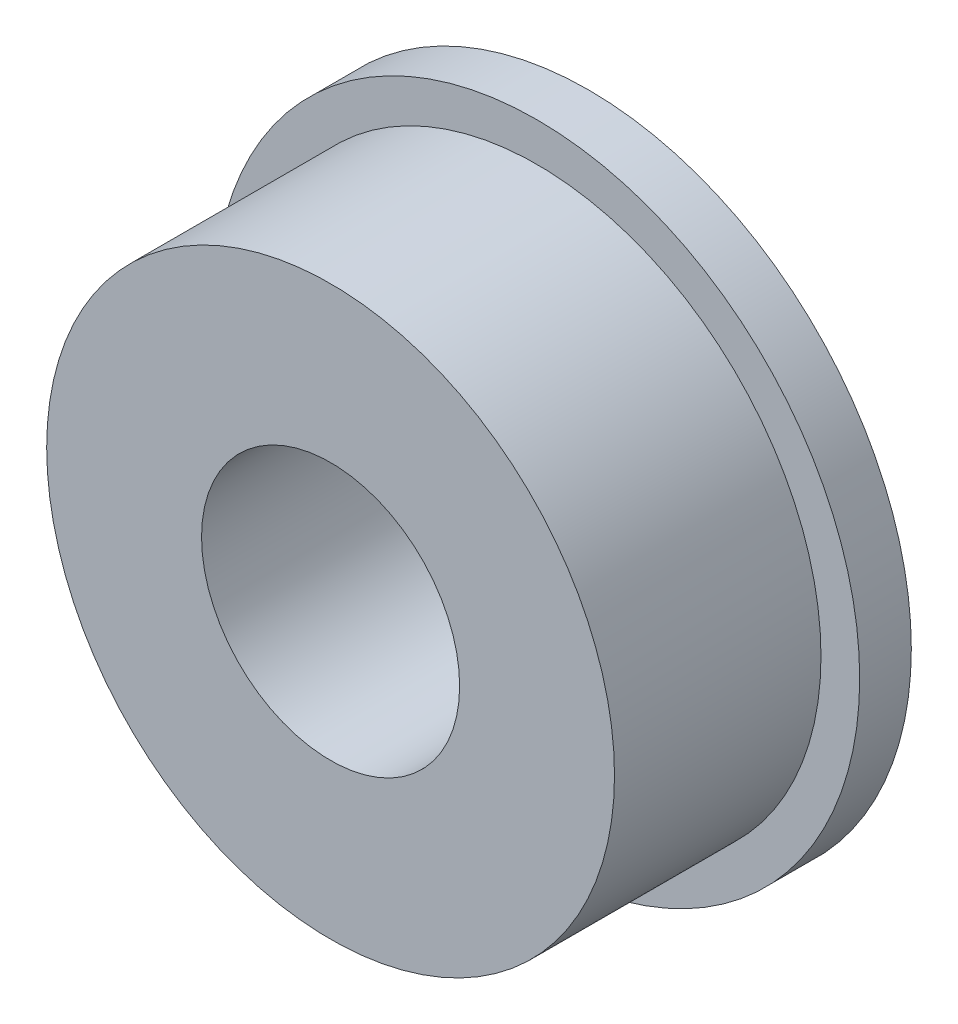
SolidWorks part; units mm, degrees
ref_plane "前视基准面" through (0, 0, 0) normal (0, 0, 1) x (1, 0, 0)
ref_plane "上视基准面" through (0, 0, 0) normal (0, 1, 0) x (1, 0, 0)
ref_plane "右视基准面" through (0, 0, 0) normal (1, 0, 0) x (0, 0, -1)
other "Configuration Table"
sketch "草图1" plane through (0, 0, 0) normal (0, 0, 1) x (1, 0, 0)
  circle A0 centre (0, 0) radius 6.25
  dimension "D1" = 12.5
extrude "凸台-拉伸1" add sketch "草图1" along normal blind 1
sketch "草图2" plane through (0, 0, 1) normal (0, 0, 1) x (1, 0, 0)
  circle A0 centre (0, 0) radius 5.5
  dimension "D1" = 11
extrude "凸台-拉伸2" add sketch "草图2" along normal blind 4
sketch "草图3" plane through (0, 0, 5) normal (0, 0, 1) x (1, 0, 0)
  circle A0 centre (0, 0) radius 2.5
  dimension "D1" = 5
extrude "切除-拉伸1" cut sketch "草图3" against normal up to surface (5 mm away) up to face at (6.25, 0, 0)
